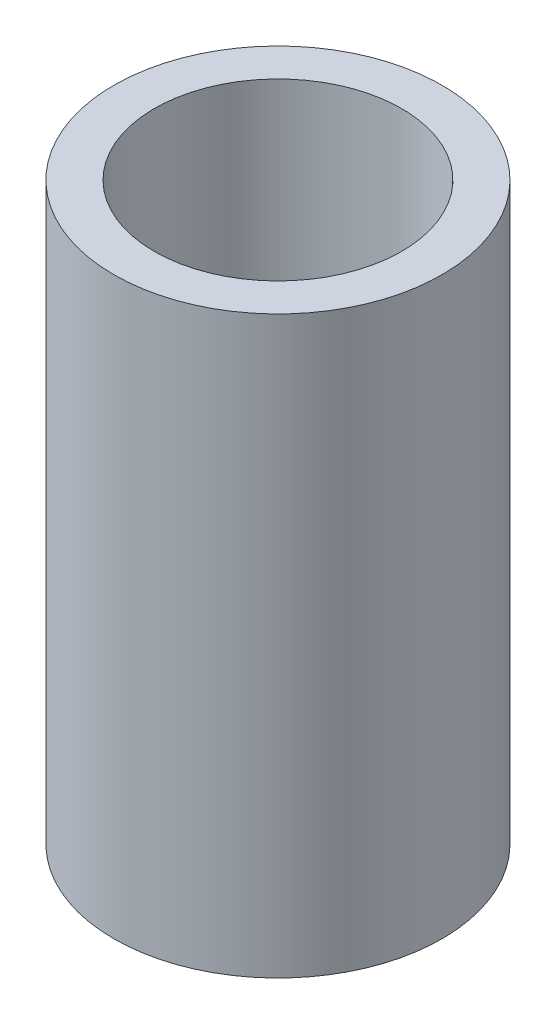
SolidWorks part; units mm, degrees
ref_plane "Front Plane" through (0, 0, 0) normal (0, 0, 1) x (1, 0, 0)
ref_plane "Top Plane" through (0, 0, 0) normal (0, 1, 0) x (1, 0, 0)
ref_plane "Right Plane" through (0, 0, 0) normal (1, 0, 0) x (0, 0, -1)
sketch "Sketch1" plane through (0, 0, 0) normal (0, 1, 0) x (1, 0, 0)
  circle A0 centre (0, 0) radius 4.7879
  circle A1 centre (0, 0) radius 6.35
  dimension "D1" = 9.5758
  dimension "D2" = 12.7
extrude "Boss-Extrude1" add sketch "Sketch1" along normal blind 22.2568
